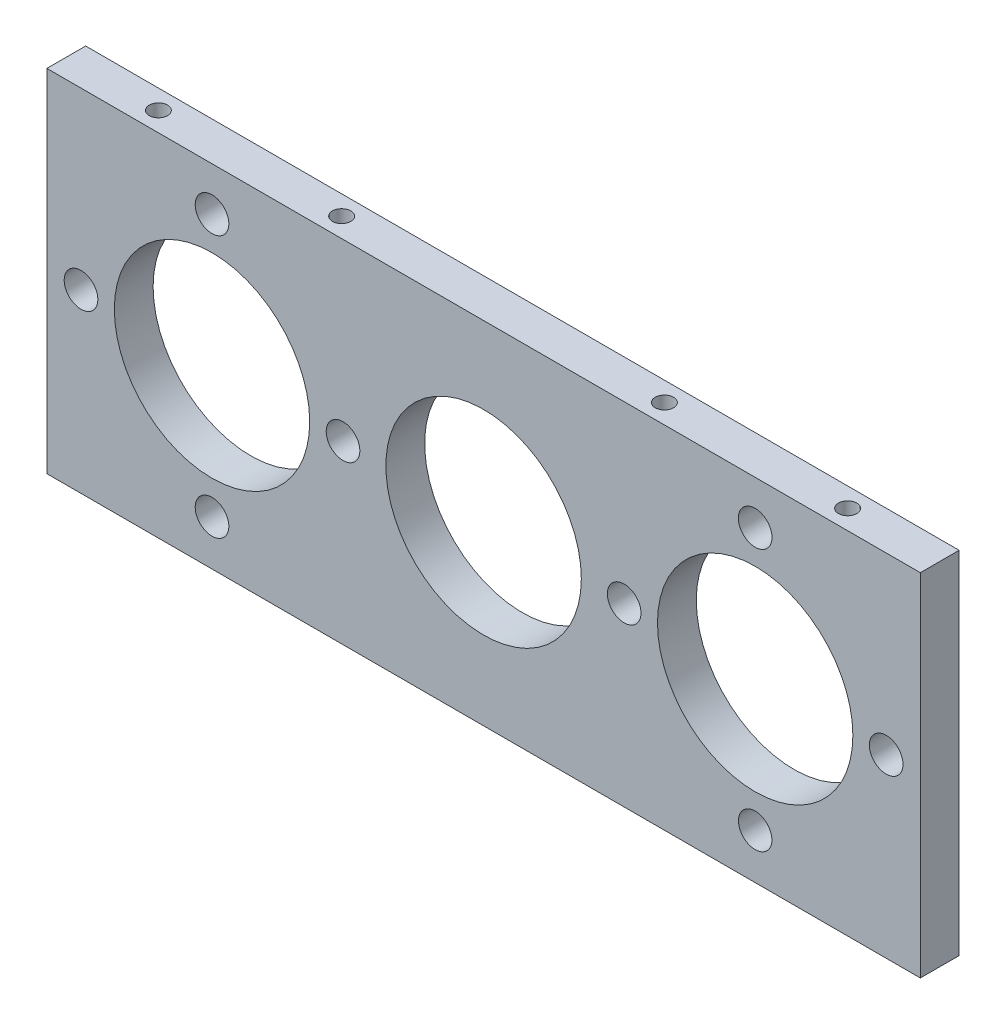
SolidWorks part; units mm, degrees
ref_plane "Plano frontal" through (0, 0, 0) normal (0, 0, 1) x (1, 0, 0)
ref_plane "Plano superior" through (0, 0, 0) normal (0, 1, 0) x (1, 0, 0)
ref_plane "Plano direito" through (0, 0, 0) normal (1, 0, 0) x (0, 0, -1)
sketch "Esboço1" plane through (0, 0, 0) normal (0, 0, 1) x (1, 0, 0)
  line L0 (71.505, 27.025) -> (-71.505, -27.025) construction
  line L1 (-71.505, 27.025) -> (71.505, 27.025)
  line L2 (-71.505, 27.025) -> (-71.505, -27.025)
  line L3 (-71.505, -27.025) -> (71.505, -27.025)
  line L4 (71.505, 27.025) -> (71.505, -27.025)
  dimension "D1" = 143.01
  dimension "D2" = 54.05
extrude "Ressalto-extrusão1" add sketch "Esboço1" along normal blind 6.35
sketch "Esboço2" plane through (0, 0, 0) normal (0, 0, -1) x (-1, 0, 0)
  circle A0 centre (-44.4631, 23.2919) radius 2.755
  circle A1 centre (-65.9131, 1.8419) radius 2.7556
  circle A2 centre (-44.4631, -19.6081) radius 2.7357
  circle A3 centre (-23.0131, 1.8419) radius 2.755
  circle A6 centre (23.0169, 1.8419) radius 2.755
  circle A9 centre (44.4669, -19.6081) radius 2.755
  circle A10 centre (65.9169, 1.8419) radius 2.755
  circle A11 centre (44.4669, 23.2919) radius 2.755
extrude "Corte-extrusão1" cut sketch "Esboço2" against normal up to surface (6.35 mm away) up to face at (0, 0, 6.35)
sketch "Esboço3" plane through (0, 0, 0) normal (0, 0, -1) x (-1, 0, 0)
  line L0 (71.505, 27.025) -> (71.505, -27.025) construction
  line L1 (-71.505, -27.025) -> (-71.505, 27.025) construction
  line L3 (71.505, -27.025) -> (-71.505, -27.025) construction
  circle A0 centre (-44.4631, 1.8419) radius 15.995
  circle A1 centre (0.0019, 1.8419) radius 10
  circle A2 centre (44.4669, 1.8419) radius 15.995
  point P15 (-5.4491, -54.0469)
  dimension "D1" = 31.99
  dimension "D2" = 31.99
  dimension "D9" = 20
  dimension "D3" = 27.0381
  dimension "D4" = 27.0419
  dimension "D5" = 28.8669
  dimension "D6" = 28.8669
  dimension "D7" = 71.5069
  dimension "D8" = 28.8669
extrude "Corte-extrusão2" cut sketch "Esboço3" against normal blind 10
sketch "Esboço4" plane through (0, 0, 0) normal (0, 0, 1) x (1, 0, 0)
  line L1 (-71.505, 27.025) -> (71.505, 27.025)
  line L2 (-71.505, 27.025) -> (-71.505, 30.445)
  line L3 (-71.505, 30.445) -> (71.505, 30.445)
  line L4 (71.505, 27.025) -> (71.505, 30.445)
  dimension "D1" = 143.01
  dimension "D2" = 3.42
extrude "Ressalto-extrusão2" add sketch "Esboço4" along normal blind 6.35
sketch "Esboço5" plane through (0, 0, 6.35) normal (0, 0, 1) x (1, 0, 0)
  line L0 (-0.0019, 11.8419) -> (-0.0019, 1.8419) construction
  circle A0 centre (-0.0019, 1.8419) radius 10 construction
  circle A1 centre (-0.0019, 1.8419) radius 16
  dimension "D1" = 32
extrude "Corte-extrusão3" cut sketch "Esboço5" against normal blind 10
sketch "Esboço6" plane through (0, 30.445, 0) normal (0, 1, 0) x (1, 0, 0)
  line L0 (71.505, -3.175) -> (-71.505, -3.175) construction
  line L1 (71.505, -6.35) -> (71.505, 0) construction
  line L2 (-71.505, -6.35) -> (-71.505, 0) construction
  line L3 (0, 0) -> (0, -3.175) construction
  line L4 (71.505, 0) -> (-71.505, 0) construction
  line L5 (71.505, -3.175) -> (-71.5868, -3.175) construction
  line L6 (0, -0.1516) -> (0, -7.1516) construction
  circle A0 centre (56.4232, -3.175) radius 1.5
  circle A1 centre (26.4232, -3.175) radius 1.5
  circle A2 centre (-26.4232, -3.175) radius 1.5
  circle A3 centre (-56.4232, -3.175) radius 1.5
  dimension "D1" = 3
  dimension "D2" = 3
extrude "Corte-extrusão4" cut sketch "Esboço6" against normal blind 15
